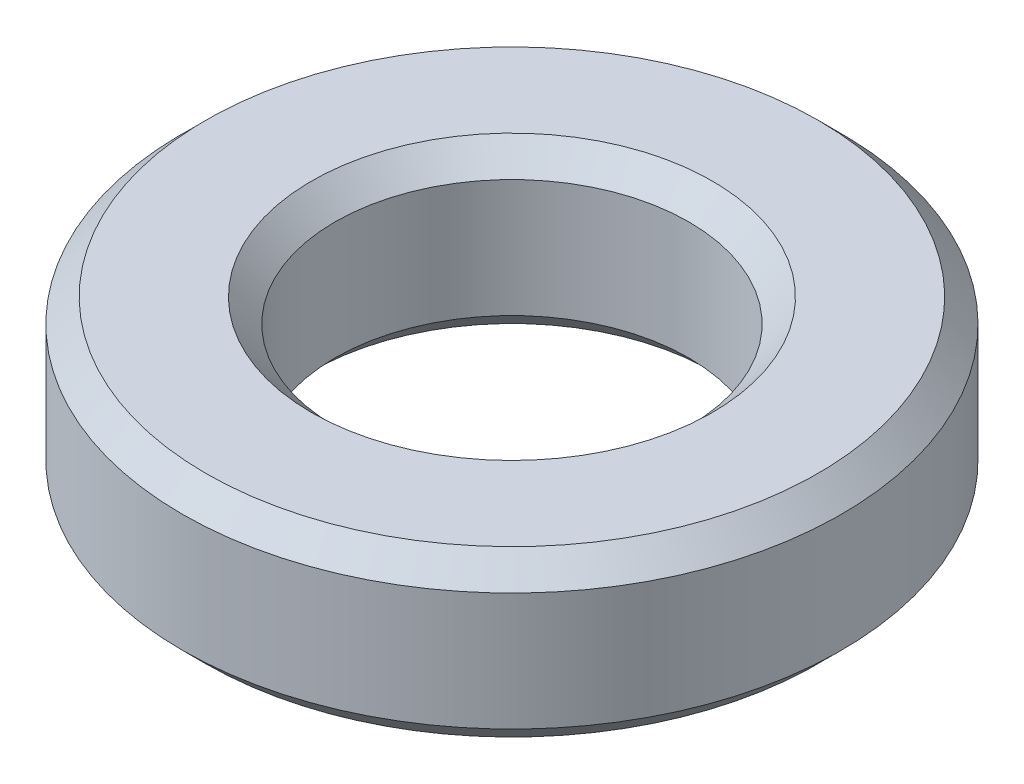
SolidWorks part; units mm, degrees
ref_plane "前视基准面" through (0, 0, 0) normal (0, 0, 1) x (1, 0, 0)
ref_plane "上视基准面" through (0, 0, 0) normal (0, 1, 0) x (1, 0, 0)
ref_plane "右视基准面" through (0, 0, 0) normal (1, 0, 0) x (0, 0, -1)
other "Configuration Table"
sketch "草图1" plane through (0, 0, 0) normal (0, 1, 0) x (1, 0, 0)
  circle A0 centre (0, 0) radius 13.99
  circle A1 centre (0, 0) radius 7.51
  dimension "D1" = 27.98
  dimension "D2" = 15.02
extrude "凸台-拉伸1" add sketch "草图1" along normal blind 7
chamfer "倒角1" distance 1 angle 45 4 edges at (0, 0, 13.99) (0, 7, 13.99) (0, 0, 7.51) (0, 7, 7.51)
